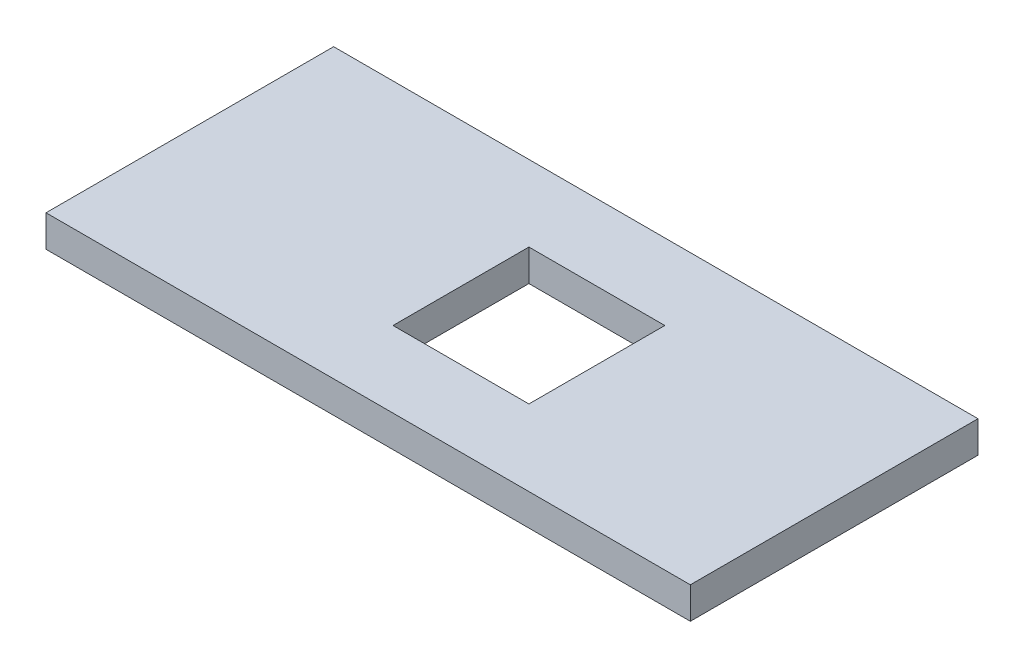
SolidWorks part; units mm, degrees
ref_plane "Front Plane" through (0, 0, 0) normal (0, 0, 1) x (1, 0, 0)
ref_plane "Top Plane" through (0, 0, 0) normal (0, 1, 0) x (1, 0, 0)
ref_plane "Right Plane" through (0, 0, 0) normal (1, 0, 0) x (0, 0, -1)
sketch "Sketch1" plane through (0, 0, 0) normal (0, 1, 0) x (1, 0, 0)
  line L1 (-142.24, -63.5) -> (142.24, -63.5)
  line L2 (-142.24, -63.5) -> (-142.24, 63.5)
  line L3 (-142.24, 63.5) -> (142.24, 63.5)
  line L4 (142.24, -63.5) -> (142.24, 63.5)
  line L5 (-142.24, -63.5) -> (142.24, 63.5) construction
  line L6 (-142.24, 63.5) -> (142.24, -63.5) construction
  point P0 (0, 0)
  dimension "D1" = 284.48
  dimension "D2" = 127
extrude "Boss-Extrude1" add sketch "Sketch1" along normal blind 13.97
sketch "Sketch2" plane through (0, 13.97, 0) normal (0, 1, 0) x (1, 0, 0)
  line L0 (142.24, 0) -> (-142.24, 0) construction
  line L1 (142.24, -63.5) -> (142.24, 63.5) construction
  line L2 (-142.24, 63.5) -> (-142.24, -63.5) construction
  line L3 (142.24, 63.5) -> (-142.24, 63.5) construction
  line L4 (-22.5324, -30) -> (37.4676, -30)
  line L5 (-22.5324, -30) -> (-22.5324, 30)
  line L6 (-22.5324, 30) -> (37.4676, 30)
  line L7 (37.4676, -30) -> (37.4676, 30)
  line L8 (-22.5324, -30) -> (37.4676, 30) construction
  line L9 (-22.5324, 30) -> (37.4676, -30) construction
  point P6 (7.4676, 0)
  dimension "D1" = 60
  dimension "D2" = 60
  dimension "D3" = 63.5
  dimension "D4" = 149.7076
extrude "Cut-Extrude1" cut sketch "Sketch2" against normal through all contours L5 L6 L7 L4
